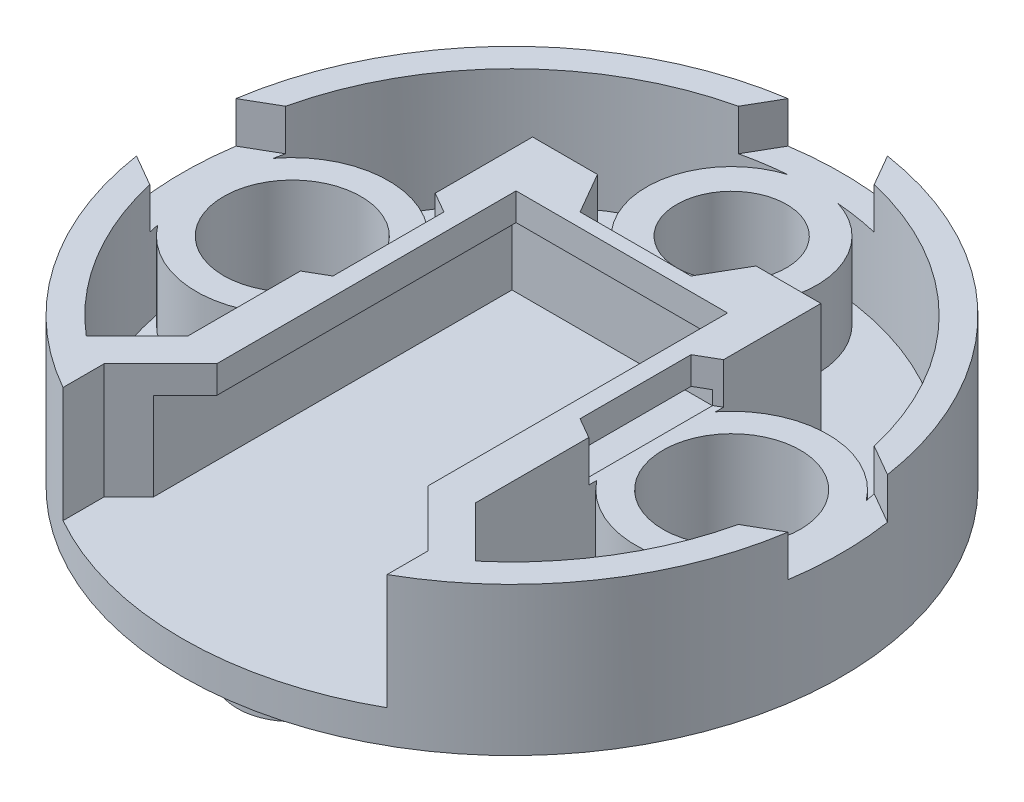
SolidWorks part; units mm, degrees
ref_plane "Front Plane" through (0, 0, 0) normal (0, 0, 1) x (1, 0, 0)
ref_plane "Top Plane" through (0, 0, 0) normal (0, 1, 0) x (1, 0, 0)
ref_plane "Right Plane" through (0, 0, 0) normal (1, 0, 0) x (0, 0, -1)
sketch "Sketch1" plane through (0, 0, 0) normal (0, 1, 0) x (1, 0, 0)
  circle A0 centre (0, 0) radius 12
  dimension "D1" = 24
extrude "Boss-Extrude1" add sketch "Sketch1" along normal blind 5.4
sketch "Sketch2" plane through (0, 5.4, 0) normal (0, 1, 0) x (1, 0, 0)
  line L1 (5, -5) -> (-5, -5) construction
  line L2 (5, -5) -> (5, 5)
  line L3 (5, 5) -> (-5, 5)
  line L4 (-5, -5) -> (-5, 5)
  line L5 (5, -5) -> (-5, 5) construction
  line L6 (5, 5) -> (-5, -5) construction
  line L8 (-5, -8.0494) -> (-5, -5)
  line L9 (5.9, -10.4494) -> (5.9, -8.9494)
  line L10 (5, -8.0494) -> (5, -5)
  line L11 (5.9, -8.9494) -> (5, -8.0494)
  line L12 (-5.9, -10.4494) -> (-5.9, -8.9494)
  line L13 (-5.9, -8.9494) -> (-5, -8.0494)
  circle A0 centre (0, 0) radius 12 construction
  arc A1 (-5.9, -10.4494) -> (5.9, -10.4494) centre (0, 0) ccw
  point P0 (0, 0)
  point P5 (0, 0)
  point P15 (0, -12)
  dimension "D1" = 10
  dimension "D2" = 10
  dimension "D3" = 11.8
  dimension "D4" = 1.5
  dimension "D5" = 45
extrude "Cut-Extrude1" cut sketch "Sketch2" against normal blind 4.2
sketch "Sketch3" plane through (0, 5.4, 0) normal (0, 1, 0) x (1, 0, 0)
  line L6 (5, -8.0494) -> (3.85, -6.8994)
  line L8 (-5, -8.0494) -> (-3.85, -6.8994)
  line L9 (-3.85, -6.8994) -> (-3.85, 4)
  line L10 (3.85, -6.8994) -> (3.85, 4)
  line L12 (5.9, -8.9494) -> (5, -8.0494) construction
  line L13 (-3.85, 4) -> (3.85, 4)
  line L14 (5, 5) -> (-5, 5) construction
  line L15 (-5, -8.0494) -> (-5, 5)
  line L16 (-5, 5) -> (5, 5)
  line L17 (5, 5) -> (5, -8.0494)
  dimension "D1" = 7.7
  dimension "D2" = 1
extrude "Boss-Extrude2" add sketch "Sketch3" against normal blind 1
sketch "Sketch4" plane through (0, 5.4, 0) normal (0, 1, 0) x (1, 0, 0)
  circle A0 centre (-8, 0) radius 2.5
  circle A1 centre (8, 0) radius 2.5
  circle A2 centre (0, 8) radius 2
  point P6 (0, 0)
  point P8 (0, 0)
  point P9 (0, 0)
  dimension "D1" = 4
  dimension "D2" = 5
  dimension "D3" = 5
  dimension "D4" = 8
  dimension "D5" = 8
  dimension "D6" = 8
extrude "Cut-Extrude2" cut sketch "Sketch4" against normal blind 11
sketch "Sketch5" plane through (0, 0, 0) normal (0, -1, 0) x (1, 0, 0)
  circle A0 centre (0, 8) radius 2
  point P2 (0, 0)
  dimension "D1" = 4
  dimension "D2" = 8
extrude "Boss-Extrude3" add sketch "Sketch5" along normal blind 2
sketch "Sketch6" plane through (0, 5.4, 0) normal (0, 1, 0) x (1, 0, 0)
  line L0 (-7.2058, -8.3112) -> (-7.2058, -8.5002)
  line L1 (-7.2058, -8.5002) -> (-5.25, -6.5445)
  line L2 (-5.25, -6.5445) -> (-5.25, 6)
  line L3 (-5.25, 6) -> (5.25, 6)
  line L4 (5.25, 6) -> (5.25, -6.5716)
  line L5 (5.25, -6.5716) -> (7.1802, -8.5018)
  line L6 (7.1802, -8.5018) -> (7.1802, -8.3333)
  line L7 (5.9, -8.9494) -> (5.9, -10.4494)
  line L8 (-5.9, -10.4494) -> (-5.9, -8.9494)
  line L9 (-5.9, -8.9494) -> (-3.85, -6.8994)
  line L10 (-3.85, -6.8994) -> (-3.85, 4)
  line L11 (-3.85, 4) -> (3.85, 4)
  line L12 (3.85, 4) -> (3.85, -6.8994)
  line L13 (3.85, -6.8994) -> (5.9, -8.9494)
  line L14 (5.9, -8.9494) -> (5.9, -10.4494) construction
  line L15 (-5.9, -10.4494) -> (-5.9, -8.9494) construction
  line L16 (-5.9, -8.9494) -> (-3.85, -6.8994) construction
  line L17 (-3.85, -6.8994) -> (-3.85, 4) construction
  line L18 (-3.85, 4) -> (3.85, 4) construction
  line L19 (3.85, 4) -> (3.85, -6.8994) construction
  line L20 (3.85, -6.8994) -> (5.9, -8.9494) construction
  arc A0 (-5.25, 2.1651) -> (-10.7969, 2.1042) centre (-8, 0) ccw
  arc A1 (5.9, -10.4494) -> (-5.9, -10.4494) centre (0, 0) ccw
  arc A2 (5.9, -10.4494) -> (-5.9, -10.4494) centre (0, 0) ccw construction
  arc A3 (2.3685, 6) -> (0.915, 10.9619) centre (0, 8) ccw
  arc A4 (5.25, -2.1651) -> (10.7969, -2.1042) centre (8, 0) ccw
  arc A5 (-10.7969, -2.1042) -> (10.7969, -2.1042) centre (0, 0) ccw
  arc A6 (-10.7969, -2.1042) -> (-5.25, -2.1651) centre (-8, 0) ccw
  arc A7 (10.7969, 2.1042) -> (5.25, 2.1651) centre (8, 0) ccw
  arc A8 (10.7969, 2.1042) -> (0.915, 10.9619) centre (0, 0) ccw
  arc A9 (-0.915, 10.9619) -> (-10.7969, 2.1042) centre (0, 0) ccw
  arc A10 (-0.915, 10.9619) -> (-2.3685, 6) centre (0, 8) ccw
  dimension "D2" = 7
  dimension "D3" = 6.2
  dimension "D4" = 7
  dimension "D5" = 22
  dimension "D6" = 2.8
  dimension "D7" = 2.8
  dimension "D8" = 2
  dimension "D1" = 0
extrude "Cut-Extrude3" cut sketch "Sketch6" against normal blind 4.3 contours A6 A5 L0 L1 L2 | L6 A5 A4 L4 L5 | A3 A8 A0 L2 L3 | A7 A8 A3 L3 L4
sketch "Sketch7" plane through (0, 5.4, 0) normal (0, 1, 0) x (1, 0, 0)
  line L0 (11.5, 2.0207) -> (12.7661, 1.2897)
  line L1 (2.0207, 4.5) -> (4.0415, 8)
  line L2 (4.0415, 8) -> (2.0207, 11.5)
  line L3 (2.0207, 11.5) -> (-2.0207, 11.5) construction
  line L4 (-2.0207, 11.5) -> (-4.0415, 8)
  line L5 (-4.0415, 8) -> (-2.0207, 4.5)
  line L6 (-2.0207, 4.5) -> (2.0207, 4.5)
  line L7 (8, 4.0415) -> (4.5, 2.0207)
  line L8 (4.5, 2.0207) -> (4.5, -2.0207)
  line L9 (4.5, -2.0207) -> (8, -4.0415)
  line L10 (8, -4.0415) -> (11.5, -2.0207)
  line L11 (11.5, -2.0207) -> (11.5, 2.0207) construction
  line L12 (11.5, 2.0207) -> (8, 4.0415)
  line L13 (-4.5, -2.0207) -> (-4.5, 2.0207)
  line L14 (-4.5, 2.0207) -> (-8, 4.0415)
  line L15 (-8, 4.0415) -> (-11.5, 2.0207)
  line L16 (-11.5, 2.0207) -> (-11.5, -2.0207) construction
  line L17 (-11.5, -2.0207) -> (-8, -4.0415)
  line L18 (-8, -4.0415) -> (-4.5, -2.0207)
  line L19 (12.7661, 1.2897) -> (12.7661, -1.2897)
  line L20 (12.7661, -1.2897) -> (11.5, -2.0207)
  line L21 (-11.5, -2.0207) -> (-12.3786, -1.5135)
  line L22 (-12.3786, -1.5135) -> (-12.3786, 1.5135)
  line L23 (-12.3786, 1.5135) -> (-11.5, 2.0207)
  line L24 (-2.0207, 11.5) -> (-1.3001, 12.7482)
  line L25 (-1.3001, 12.7482) -> (1.3001, 12.7482)
  line L26 (1.3001, 12.7482) -> (2.0207, 11.5)
  circle A0 centre (0, 8) radius 3.5 construction
  circle A1 centre (8, 0) radius 3.5 construction
  circle A2 centre (-8, 0) radius 3.5 construction
  circle A3 centre (8, 0) radius 2.5 construction
  dimension "D1" = 7
extrude "Cut-Extrude4" cut sketch "Sketch7" against normal blind 1.5
